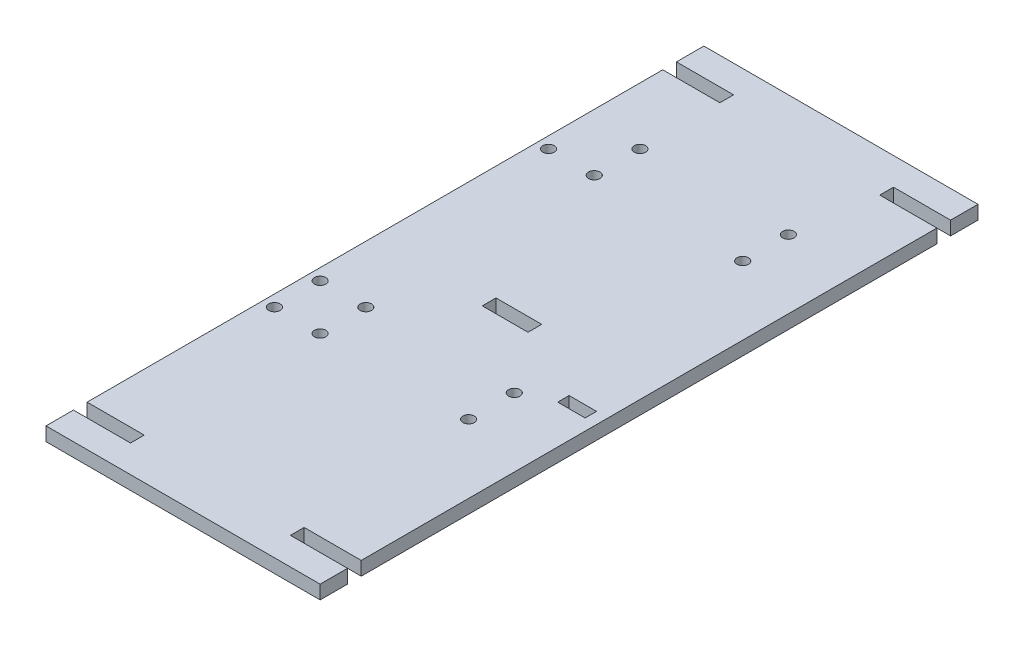
SolidWorks part; units mm, degrees
ref_plane "Front" through (0, 0, 0) normal (0, 0, 1) x (1, 0, 0)
ref_plane "Top" through (0, 0, 0) normal (0, 1, 0) x (1, 0, 0)
ref_plane "Right" through (0, 0, 0) normal (1, 0, 0) x (0, 0, -1)
sketch "Sketch1" plane through (0, 0, 0) normal (0, 1, 0) x (1, 0, 0)
  line L1 (0, 0) -> (-120, 0)
  line L2 (0, 0) -> (0, 288)
  line L3 (0, 288) -> (-120, 288)
  line L4 (-120, 0) -> (-120, 288)
  dimension "D1" = 288
  dimension "D2" = 120
extrude "Boss-Extrude1" add sketch "Sketch1" along normal blind 6
sketch "Sketch2" plane through (0, 6, 0) normal (0, 1, 0) x (1, 0, 0)
  line L0 (-120, 288) -> (-120, 0) construction
  line L1 (-120, 276) -> (-95, 276)
  line L2 (-120, 276) -> (-120, 270)
  line L3 (-120, 270) -> (-95, 270)
  line L4 (-95, 276) -> (-95, 270)
  line L5 (0, 288) -> (-120, 288) construction
  dimension "D1" = 6
  dimension "D2" = 25
  dimension "D3" = 12
extrude "Cut-Extrude1" cut sketch "Sketch2" against normal through all
pattern_linear "LPattern1" count 2 spacing 258 along (0, 0, 1) count 2 spacing 95 along (1, 0, 0) of "Cut-Extrude1"
sketch "Sketch3" plane through (0, 6, 0) normal (0, 1, 0) x (1, 0, 0)
  line L0 (-60, 288) -> (-60, 0) construction
  line L1 (0, 288) -> (-120, 288) construction
  line L2 (-120, 0) -> (0, 0) construction
  line L3 (-120, 144) -> (0, 144) construction
  line L4 (-120, 270) -> (-120, 18) construction
  line L5 (0, 18) -> (0, 270) construction
  line L7 (-70, 141) -> (-50, 141)
  line L8 (-70, 141) -> (-70, 147)
  line L9 (-70, 147) -> (-50, 147)
  line L10 (-50, 141) -> (-50, 147)
  line L11 (-70, 141) -> (-50, 147) construction
  line L12 (-70, 147) -> (-50, 141) construction
  point P12 (-60, 144)
  dimension "D1" = 6
  dimension "D2" = 20
extrude "Cut-Extrude2" cut sketch "Sketch3" against normal blind 10
sketch "Sketch4" plane through (0, 6, 0) normal (0, 1, 0) x (1, 0, 0)
  line L0 (-105, 115) -> (-105, 215) construction
  line L1 (-30, 235) -> (-30, 215) construction
  line L2 (-95, 225) -> (-30, 225) construction
  line L3 (-95, 105) -> (-30, 105) construction
  line L4 (-70, 141) -> (-50, 141) construction
  line L5 (-105, 105) -> (-105, 55) construction
  line L6 (-120, 270) -> (-120, 18) construction
  line L7 (-115, 115) -> (-95, 115) construction
  line L8 (-95, 115) -> (-95, 95) construction
  line L9 (-30, 115) -> (-30, 95) construction
  line L10 (-115, 115) -> (-115, 95) construction
  line L11 (-115, 95) -> (-95, 95) construction
  arc A0 (-105, 115) -> (-95, 105) centre (-95, 115) ccw construction
  arc A1 (-105, 215) -> (-95, 225) centre (-95, 215) cw construction
  circle A2 centre (-30, 235) radius 2.5
  circle A3 centre (-30, 215) radius 2.5
  circle A4 centre (-95, 235) radius 2.5
  circle A5 centre (-95, 215) radius 2.5
  circle A6 centre (-115, 215) radius 2.5
  circle A13 centre (-95, 115) radius 2.5
  circle A14 centre (-115, 115) radius 2.5
  circle A15 centre (-95, 95) radius 2.5
  circle A16 centre (-30, 115) radius 2.5
  circle A17 centre (-30, 95) radius 2.5
  circle A18 centre (-115, 95) radius 2.5
  point P11 (-120, 144)
  point P15 (-105, 225)
  point P17 (-95, 225)
  point P18 (-105, 215)
  point P19 (-105, 115)
  point P20 (-95, 105)
  point P21 (-30, 105)
  point P23 (-30, 225)
  point P26 (-95, 105)
  point P32 (-105, 115)
  point P35 (-95, 215)
  point P39 (-30, 105)
  dimension "D6" = 10
  dimension "D7" = 5
  dimension "D1" = 36
  dimension "D2" = 50
  dimension "D3" = 75
  dimension "D4" = 15
  dimension "D5" = 120
  dimension "D8" = 20
  dimension "D9" = 2
  dimension "D10" = 2
extrude "Cut-Extrude4" cut sketch "Sketch4" against normal blind 10
sketch "Sketch6" plane through (0, 6, 0) normal (0, 1, 0) x (1, 0, 0)
  line L0 (0, 18) -> (0, 270) construction
  line L1 (-5, 126) -> (-17, 126)
  line L2 (-5, 126) -> (-5, 121)
  line L3 (-5, 121) -> (-17, 121)
  line L4 (-17, 126) -> (-17, 121)
  line L5 (-70, 141) -> (-50, 141) construction
  dimension "D1" = 5
  dimension "D2" = 12
  dimension "D3" = 5
  dimension "D4" = 15
extrude "Cut-Extrude5" cut sketch "Sketch6" against normal blind 10
